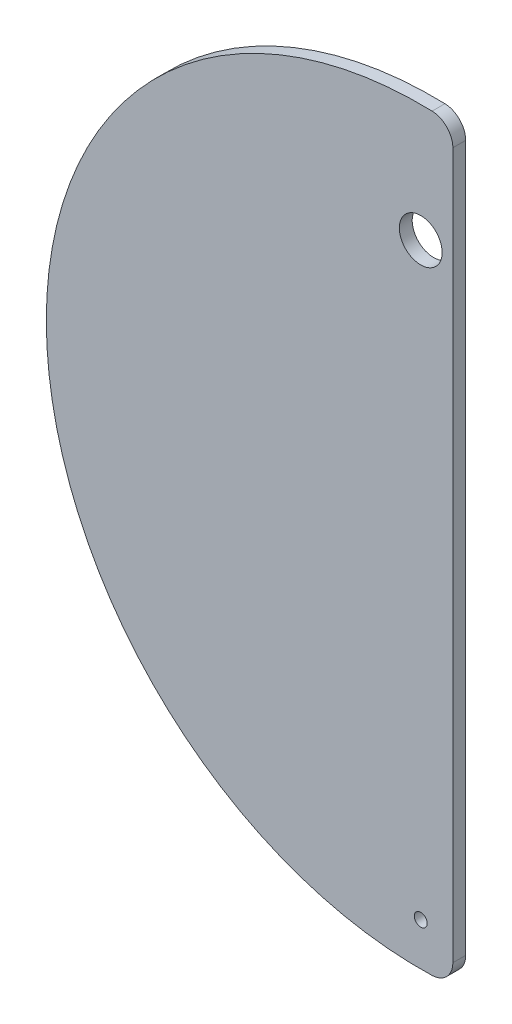
SolidWorks part; units mm, degrees
ref_plane "Front Plane" through (0, 0, 0) normal (0, 0, 1) x (1, 0, 0)
ref_plane "Top Plane" through (0, 0, 0) normal (0, 1, 0) x (1, 0, 0)
ref_plane "Right Plane" through (0, 0, 0) normal (1, 0, 0) x (0, 0, -1)
sketch "Sketch1" plane through (0, 0, 0) normal (0, 0, 1) x (1, 0, 0)
  line L0 (0, 233.0999) -> (0, -220.1999) construction
  line L1 (15, 174.356) -> (15, -174.356)
  line L2 (15, 233.0999) -> (15, -220.1999) construction
  arc A0 (15, 174.356) -> (15, -174.356) centre (0, 0) ccw
  circle A1 centre (0, 120) radius 10
  circle A2 centre (0, -155) radius 3
  dimension "D1" = 350
  dimension "D2" = 20
  dimension "D5" = 6
  dimension "D6" = 275
  dimension "D4" = 120
  dimension "D3" = 15
extrude "Boss-Extrude1" add sketch "Sketch1" along normal blind 6
fillet "Fillet1" radius 10 2 edges at (15, 174.356, 3) (15, -174.356, 3)
